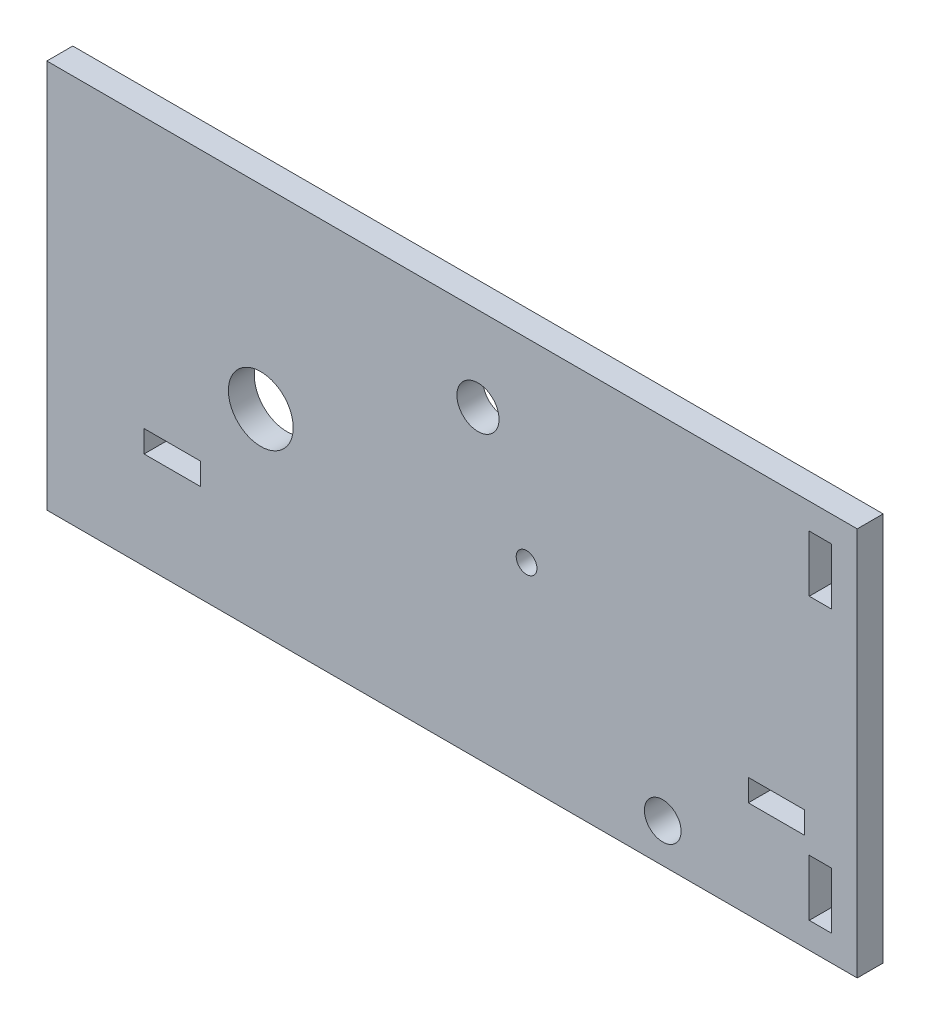
SolidWorks part; units mm, degrees
ref_plane "Front Plane" through (0, 0, 0) normal (0, 0, 1) x (1, 0, 0)
ref_plane "Top Plane" through (0, 0, 0) normal (0, 1, 0) x (1, 0, 0)
ref_plane "Right Plane" through (0, 0, 0) normal (1, 0, 0) x (0, 0, -1)
sketch "Sketch1" plane through (0, 0, 0) normal (0, 0, 1) x (1, 0, 0)
  line L1 (-79, -30) -> (42, -30)
  line L2 (-79, -30) -> (-79, 30)
  line L3 (-79, 30) -> (42, 30)
  line L4 (42, -30) -> (42, 30)
  line L5 (-64, -11.6) -> (-55.3, -11.6)
  line L6 (-64, -11.6) -> (-64, -15)
  line L7 (-64, -15) -> (-55.3, -15)
  line L8 (-55.3, -11.6) -> (-55.3, -15)
  line L9 (29.2, -11.6) -> (37.9, -11.6)
  line L10 (29.2, -11.6) -> (29.2, -15)
  line L11 (29.2, -15) -> (37.9, -15)
  line L12 (37.9, -11.6) -> (37.9, -15)
  circle A2 centre (-46, 0) radius 5
  circle A3 centre (-12.5, 17) radius 3.25
  circle A4 centre (16, -24) radius 2.83
  circle A5 centre (-5, 0) radius 1.6
  point P1 (0, 0)
  point P6 (0, 0)
  point P22 (-55.3, -13.3)
  point P24 (-79, 0)
  dimension "D3" = 15
  dimension "D4" = 121
  dimension "D5" = 33
  dimension "D6" = 8.7
  dimension "D7" = 33.5
  dimension "D10" = 6.5
  dimension "D12" = 95
  dimension "D13" = 6
  dimension "D14" = 5.66
  dimension "D15" = 54.5
  dimension "D18" = 41
  dimension "D19" = 17
  dimension "D20" = 10
  dimension "D21" = 10
  dimension "D2" = 60
  dimension "D8" = 3.4
  dimension "D9" = 15
  dimension "D11" = 15
  dimension "D16" = 84.5
extrude "Boss-Extrude1" add sketch "Sketch1" along normal blind 4
sketch "Sketch2" plane through (0, 0, 0) normal (0, 0, 1) x (1, 0, 0)
  line L0 (42, 30) -> (46, 30)
  line L1 (46, 30) -> (46, -30)
  line L2 (46, -30) -> (42, -30)
  line L13 (-79, -30) -> (42, -30) construction
  line L14 (42, -30) -> (42, 30)
  dimension "D1" = 4
extrude "Boss-Extrude2" add sketch "Sketch2" along normal blind 4
sketch "Sketch3" plane through (0, 0, 0) normal (0, 0, 1) x (1, 0, 0)
  line L0 (46, -30) -> (46, 30) construction
  line L1 (38.6, 26) -> (42, 26)
  line L2 (38.6, 26) -> (38.6, 17.3)
  line L3 (38.6, 17.3) -> (42, 17.3)
  line L4 (42, 26) -> (42, 17.3)
  line L5 (38.6, -17.3) -> (42, -17.3)
  line L6 (38.6, -17.3) -> (38.6, -26)
  line L7 (38.6, -26) -> (42, -26)
  line L8 (42, -17.3) -> (42, -26)
  line L9 (46, 30) -> (-79, 30) construction
  line L10 (-79, -30) -> (46, -30) construction
  dimension "D1" = 4
  dimension "D2" = 3.4
  dimension "D3" = 8.7
  dimension "D4" = 4
  dimension "D5" = 4
extrude "Cut-Extrude2" cut sketch "Sketch3" along normal through all both
equation "\"padding\"=4"
equation "\"hole_width\"=3.4"
equation "\"hole_height\"=8.7"
equation "\"D1@Sketch3\"=\"padding\""
equation "\"D2@Sketch3\"=\"hole_width\""
equation "\"D3@Sketch3\"=\"hole_height\""
equation "\"D4@Sketch3\"=\"padding\""
equation "\"D5@Sketch3\"=\"padding\""
